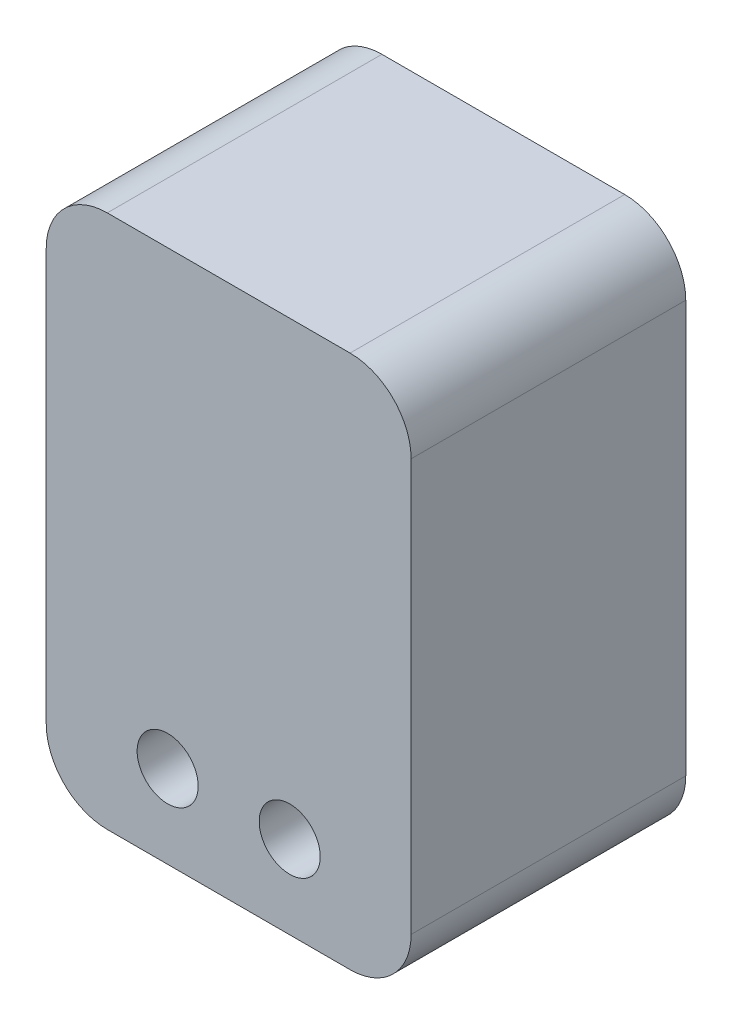
SolidWorks part; units mm, degrees
ref_plane "Front" through (0, 0, 0) normal (0, 0, 1) x (1, 0, 0)
ref_plane "Top" through (0, 0, 0) normal (0, 1, 0) x (1, 0, 0)
ref_plane "Right" through (0, 0, 0) normal (1, 0, 0) x (0, 0, -1)
sketch "Sketch1" plane through (0, 0, 0) normal (0, 0, 1) x (1, 0, 0)
  line L0 (-2, -6.0324) -> (2, -6.0324) construction
  line L1 (-5.9788, 8.75) -> (5.9788, 8.75)
  line L2 (-5.9788, 8.75) -> (-5.9788, -8.75)
  line L3 (-5.9788, -8.75) -> (5.9788, -8.75)
  line L4 (5.9788, 8.75) -> (5.9788, -8.75)
  line L5 (-5.9788, 8.75) -> (5.9788, -8.75) construction
  line L6 (-5.9788, -8.75) -> (5.9788, 8.75) construction
  line L7 (0, -55) -> (0, 55) construction
  circle A0 centre (-2, -6.0324) radius 1
  circle A1 centre (2, -6.0324) radius 1
  point P0 (0, 0)
  point P10 (0, -6.0324)
  dimension "D1" = 2
  dimension "D2" = 4
  dimension "D3" = 17.5
  dimension "D4" = 2.7176
extrude "Boss-Extrude1" add sketch "Sketch1" along normal blind 9
sketch "Sketch2" plane through (0, 8.75, 0) normal (0, 1, 0) x (1, 0, 0)
  line L0 (0, -55) -> (0, 55) construction
  line L1 (5.9788, -9) -> (5.9788, 0) construction
  circle A0 centre (0, -4.5) radius 3.5
  point P6 (5.9788, -4.5)
  dimension "D1" = 7
extrude "Cut-Extrude1" cut sketch "Sketch2" against normal blind 3.7 from offset 2 offset against normal yes
fillet "Fillet1" radius 2 4 edges at (5.9788, 8.75, 4.5) (5.9788, -8.75, 4.5) (-5.9788, -8.75, 4.5) (-5.9788, 8.75, 4.5)
